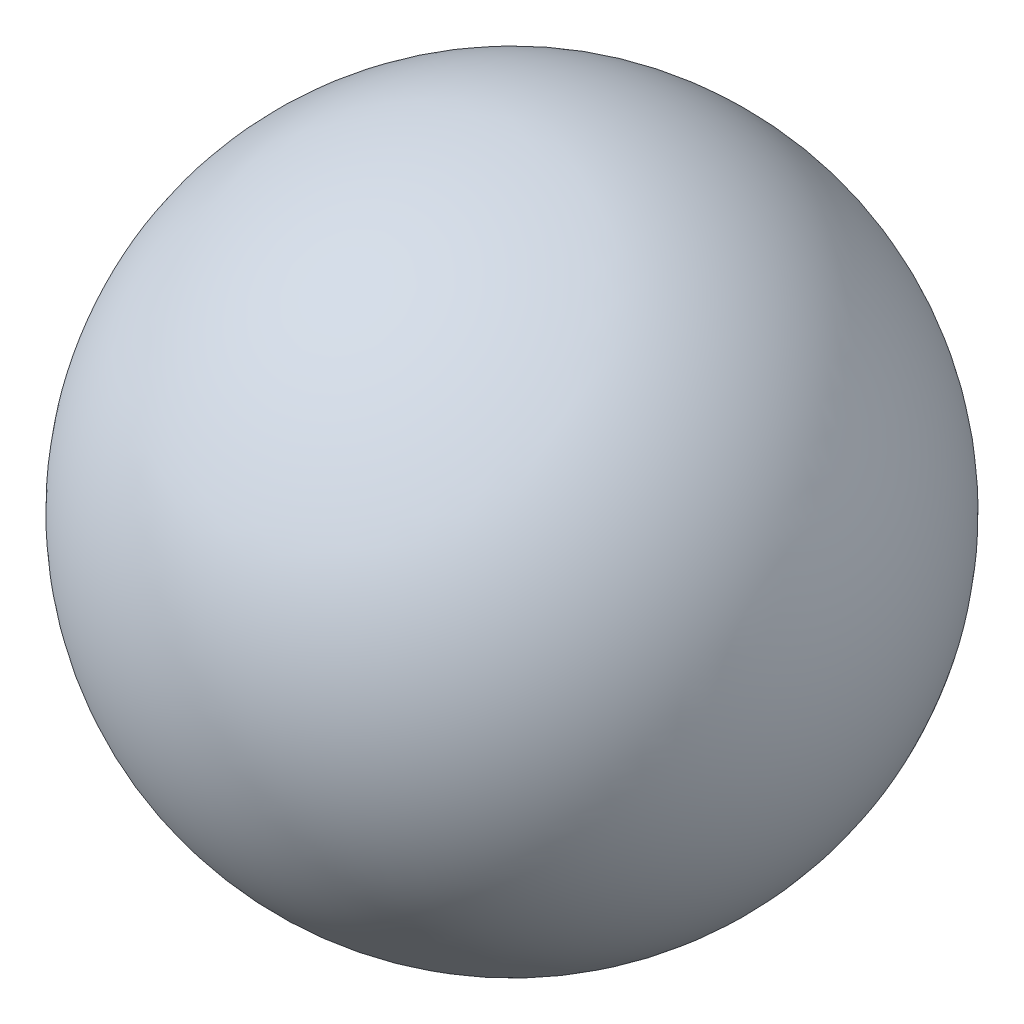
SolidWorks part; units mm, degrees
material "NEOPRENE"
ref_plane "Front Plane" through (0, 0, 0) normal (0, 0, 1) x (1, 0, 0)
ref_plane "Top Plane" through (0, 0, 0) normal (0, 1, 0) x (1, 0, 0)
ref_plane "Right Plane" through (0, 0, 0) normal (1, 0, 0) x (0, 0, -1)
sketch "Sketch2" plane through (0, 0, 0) normal (0, 1, 0) x (1, 0, 0)
  line L1 (980.9957, 79.9725) -> (987.3247, 80.4884)
  line L2 (-987.3247, -80.4884) -> (-980.9957, -79.9725)
  arc A0 (-987.3247, -80.4884) -> (987.3247, 80.4884) centre (0, 0) ccw
  arc A1 (-980.9957, -79.9725) -> (980.9957, 79.9725) centre (0, 0) ccw
  dimension "D1" = 990.6
revolve "Revolve2" add sketch "Sketch2" angle 360 about L2
